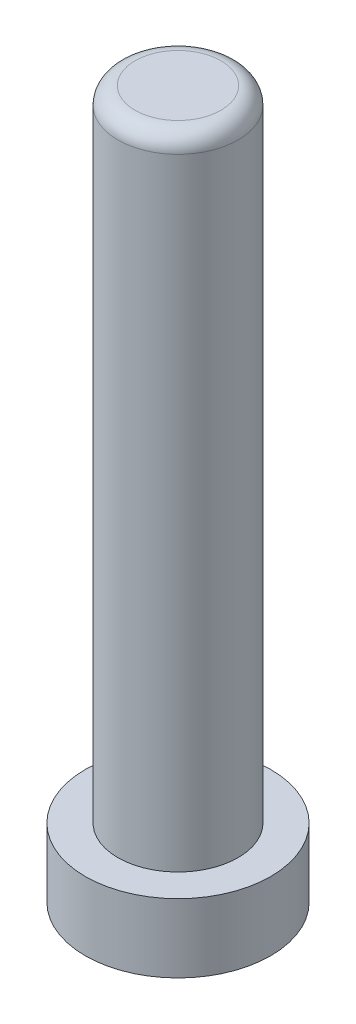
SolidWorks part; units mm, degrees
ref_plane "Front Plane" through (0, 0, 0) normal (0, 0, 1) x (1, 0, 0)
ref_plane "Top Plane" through (0, 0, 0) normal (0, 1, 0) x (1, 0, 0)
ref_plane "Right Plane" through (0, 0, 0) normal (1, 0, 0) x (0, 0, -1)
sketch "Sketch1" plane through (0, 0, 0) normal (0, 1, 0) x (1, 0, 0)
  line L1 (-2.8, -2.7) -> (2.8, -2.7) construction
  line L2 (-2.8, -2.7) -> (-2.8, 2.7) construction
  line L3 (-2.8, 2.7) -> (2.8, 2.7) construction
  line L4 (2.8, -2.7) -> (2.8, 2.7) construction
  line L5 (-2.8, -2.7) -> (2.8, 2.7) construction
  line L6 (-2.8, 2.7) -> (2.8, -2.7) construction
  circle A0 centre (0, 0) radius 2.7
  point P0 (0, 0)
  dimension "D1" = 5.6
  dimension "D2" = 5.4
extrude "Boss-Extrude1" add sketch "Sketch1" along normal blind 2
sketch "Sketch2" plane through (0, 2, 0) normal (0, 1, 0) x (1, 0, 0)
  circle A0 centre (0, 0) radius 1.75
  dimension "D1" = 3.5
sketch "Sketch3" plane through (0, 0, 0) normal (0, -1, 0) x (1, 0, 0)
  circle A0 centre (0, 0) radius 1.2
  circle A1 centre (0, 0) radius 0.95
  point P0 (0, 0)
  dimension "D1" = 2.4
  dimension "D2" = 1.9
extrude "Cut-Extrude2" cut sketch "Sketch3" against normal blind 9.5 contours A1
extrude "Boss-Extrude2" add sketch "Sketch2" along normal blind 18.6
sketch "Sketch7" plane through (0, 0, 0) normal (0, -1, 0) x (1, 0, 0)
  circle A0 centre (0, 0) radius 1.2
  dimension "D1" = 2.4
extrude "Cut-Extrude4" cut sketch "Sketch7" against normal blind 2.8
fillet "Fillet2" radius 0.5 1 edges at (0, 20.6, 1.75)
sketch "Sketch8" plane through (0, 0, 0) normal (0, -1, 0) x (1, 0, 0)
  circle A0 centre (0, 0) radius 0.85
  dimension "D1" = 1.7
extrude "Cut-Extrude5" cut sketch "Sketch8" against normal blind 10.5
